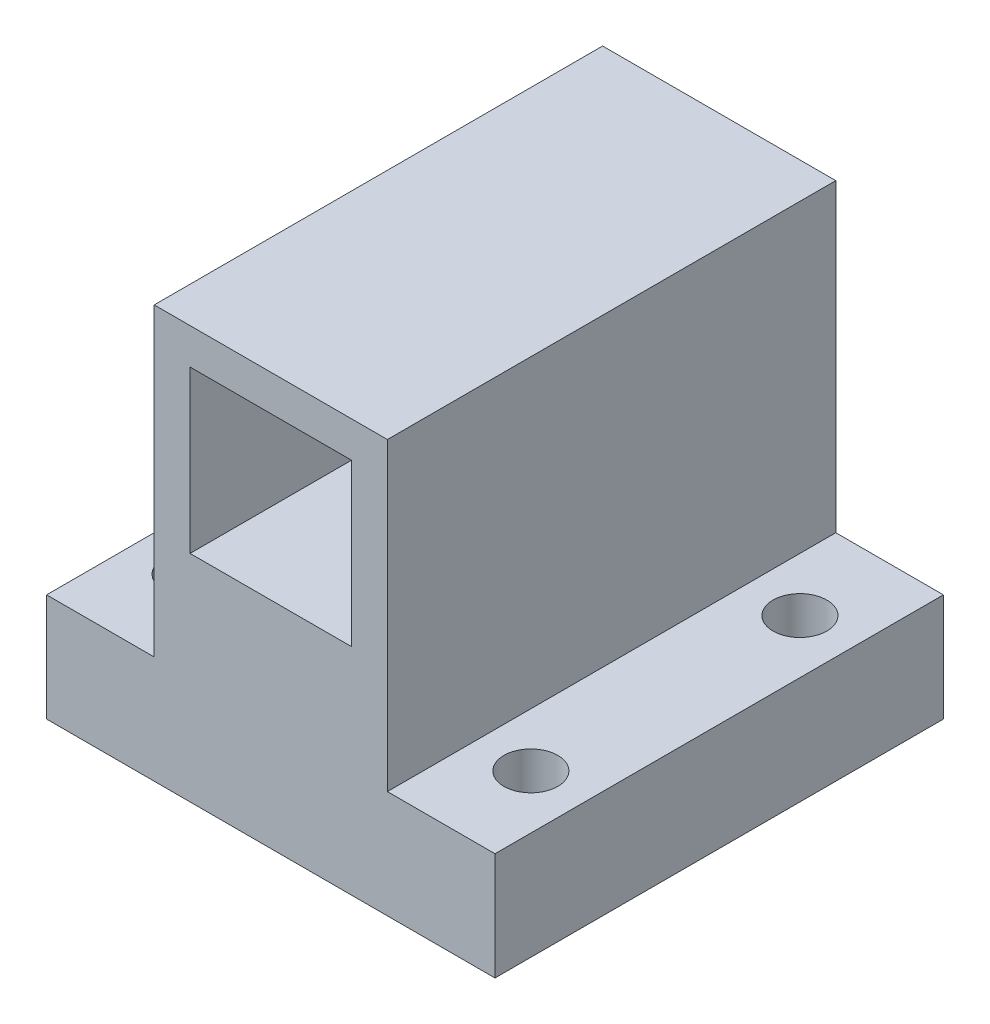
SolidWorks part; units mm, degrees
ref_plane "前视基准面" through (0, 0, 0) normal (0, 0, 1) x (1, 0, 0)
ref_plane "上视基准面" through (0, 0, 0) normal (0, 1, 0) x (1, 0, 0)
ref_plane "右视基准面" through (0, 0, 0) normal (1, 0, 0) x (0, 0, -1)
sketch "草图1" plane through (0, 0, 0) normal (0, 1, 0) x (1, 0, 0)
  line L1 (-72.4587, -32.421) -> (-47.4587, -32.421)
  line L2 (-72.4587, -32.421) -> (-72.4587, -57.421)
  line L3 (-72.4587, -57.421) -> (-47.4587, -57.421)
  line L4 (-47.4587, -32.421) -> (-47.4587, -57.421)
  line L5 (-72.4587, -32.421) -> (-47.4587, -57.421) construction
  line L6 (-72.4587, -57.421) -> (-47.4587, -32.421) construction
  point P0 (-59.9587, -44.921)
  dimension "D1" = 25
extrude "凸台-拉伸1" add sketch "草图1" along normal blind 23
sketch "草图2" plane through (0, 23, 0) normal (0, 1, 0) x (1, 0, 0)
  line L0 (-72.4587, -32.421) -> (-66.4587, -32.421)
  line L1 (-47.4587, -32.421) -> (-72.4587, -32.421) construction
  line L2 (-66.4587, -32.421) -> (-66.4587, -57.421)
  line L3 (-72.4587, -57.421) -> (-47.4587, -57.421) construction
  line L4 (-66.4587, -57.421) -> (-72.4587, -57.421)
  line L5 (-72.4587, -57.421) -> (-72.4587, -32.421)
  line L6 (-47.4587, -32.421) -> (-47.4587, -57.421)
  line L7 (-47.4587, -57.421) -> (-53.4587, -57.421)
  line L8 (-53.4587, -57.421) -> (-53.4587, -32.421)
  line L9 (-53.4587, -32.421) -> (-47.4587, -32.421)
  dimension "D1" = 6
  dimension "D2" = 6
extrude "切除-拉伸1" cut sketch "草图2" against normal blind 17
sketch "草图3" plane through (0, 6, 0) normal (0, 1, 0) x (1, 0, 0)
  circle A0 centre (-69.4587, -37.421) radius 1.5
  circle A1 centre (-69.4587, -52.421) radius 1.5
  dimension "D2" = 3
  dimension "D4" = 3
extrude "切除-拉伸2" cut sketch "草图3" against normal blind 6
ref_plane "基准面1" through (-59.9587, 0, 0) normal (-1, 0, 0) x (0, 0, 1)
mirror "镜向1" about plane through (-59.9587, 0, 0) normal (-1, 0, 0) of "切除-拉伸2"
sketch "草图4" plane through (0, 0, 57.421) normal (0, 0, 1) x (1, 0, 0)
  line L3 (-64.4587, 21) -> (-55.4587, 21)
  line L4 (-55.4587, 21) -> (-55.4587, 12)
  line L5 (-55.4587, 12) -> (-64.4587, 12)
  line L6 (-64.4587, 12) -> (-64.4587, 21)
  line L7 (-64.4587, 21) -> (-64.5894, 20.8959)
  dimension "D3" = 9
  dimension "D4" = 9
sketch "草图7" plane through (0, 0, 57.421) normal (0, 0, 1) x (1, 0, 0)
  line L0 (-64.4587, 21) -> (-55.4587, 21)
  line L1 (-55.4587, 21) -> (-55.4587, 12)
  line L2 (-55.4587, 12) -> (-64.4587, 12)
  line L3 (-64.4587, 12) -> (-64.4587, 21)
extrude "切除-拉伸3" cut sketch "草图7" against normal blind 23
sketch "草图8" plane through (0, 0, 34.421) normal (0, 0, 1) x (1, 0, 0)
  line L0 (-59.9587, 11.55) -> (-59.9587, -11.55) construction
  circle A0 centre (-59.9587, 16.5) radius 3.1
  dimension "D1" = 6.2
extrude "切除-拉伸4" cut sketch "草图8" against normal blind 23
ref_plane "基准面2" through (0, 0, 63.821) normal (0, 0, -1) x (-1, 0, 0)
sketch "草图9" plane through (0, 0, 63.821) normal (0, 0, -1) x (-1, 0, 0)
  line L0 (62.3259, 3.815) -> (58.1786, 14.6242)
sketch "草图10" plane through (0, 0, 57.421) normal (0, 0, 1) x (1, 0, 0)
  line L0 (-47.4587, 6) -> (-47.4587, 0) construction
  line L1 (-72.4587, -3) -> (-47.4587, -3)
  line L2 (-72.4587, -3) -> (-72.4587, 23)
  line L3 (-72.4587, 23) -> (-47.4587, 23)
  line L4 (-47.4587, -3) -> (-47.4587, 23)
  line L5 (-66.4587, 23) -> (-53.4587, 23) construction
  line L6 (-72.4587, 6) -> (-72.4587, 0) construction
  line L7 (-72.4587, 0) -> (-47.4587, 0) construction
  dimension "D1" = 3
